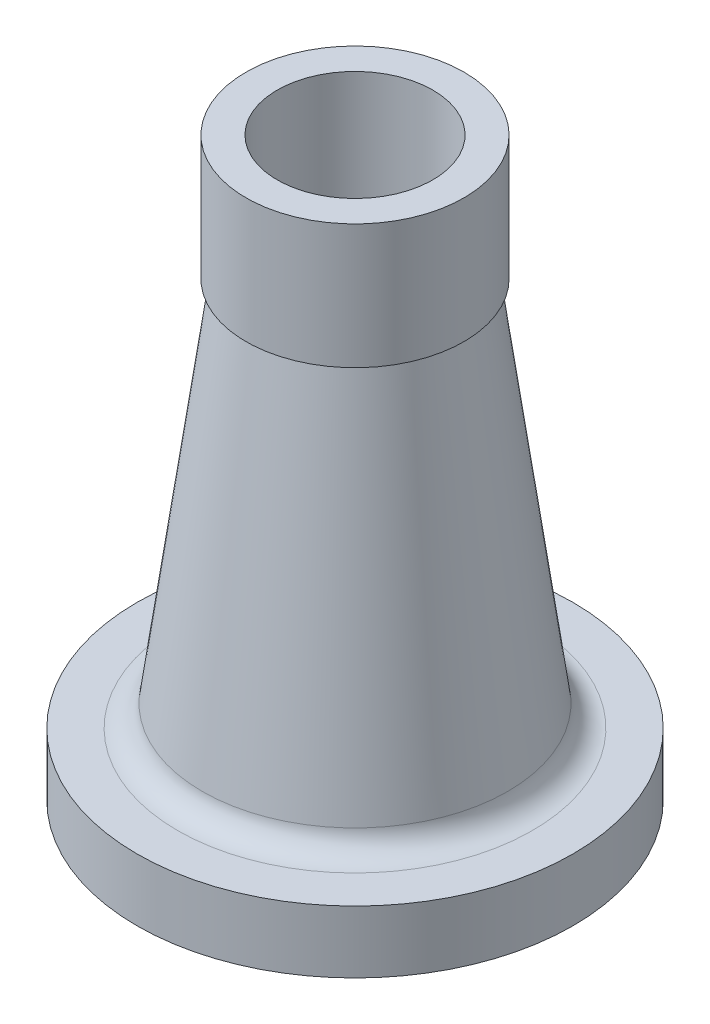
SolidWorks part; units mm, degrees
material "Gray Cast Iron"
ref_plane "Front Plane" through (0, 0, 0) normal (0, 0, 1) x (1, 0, 0)
ref_plane "Top Plane" through (0, 0, 0) normal (0, 1, 0) x (1, 0, 0)
ref_plane "Right Plane" through (0, 0, 0) normal (1, 0, 0) x (0, 0, -1)
sketch "Sketch3" plane through (0, 0, 0) normal (0, 0, 1) x (1, 0, 0)
  line L0 (50, 0) -> (70, 0)
  line L1 (70, 0) -> (70, 20)
  line L2 (70, 20) -> (50, 20)
  line L3 (50, 20) -> (33, 145)
  line L4 (33, 145) -> (35, 145)
  line L5 (35, 145) -> (35, 185)
  line L6 (35, 185) -> (25, 185)
  line L7 (25, 185) -> (25, 129.6172)
  line L8 (25, 129.6172) -> (42.2199, 3)
  line L9 (42.2199, 3) -> (50, 3)
  line L10 (50, 3) -> (50, 0)
  line L11 (0, 0) -> (0, 185) construction
  point P14 (25, 132.942)
  dimension "D1" = 70
  dimension "D2" = 50
  dimension "D3" = 35
  dimension "D4" = 25
  dimension "D5" = 33
  dimension "D6" = 20
  dimension "D7" = 50
  dimension "D8" = 3
  dimension "D9" = 185
  dimension "D10" = 185
  dimension "D11" = 40
  dimension "D12" = 10
revolve "Revolve1" add sketch "Sketch3" angle 360 about L11
fillet "Fillet1" radius 8 1 edges at (0, 20, -50)
